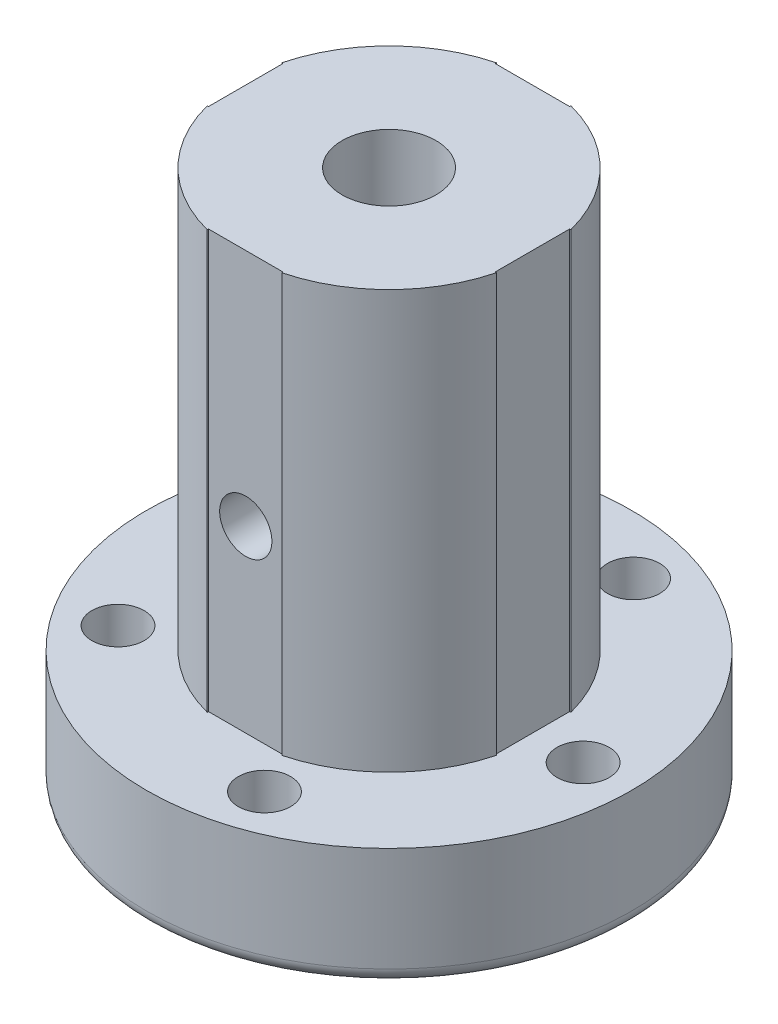
SolidWorks part; units mm, degrees
ref_plane "Front Plane" through (0, 0, 0) normal (0, 0, 1) x (1, 0, 0)
ref_plane "Top Plane" through (0, 0, 0) normal (0, 1, 0) x (1, 0, 0)
ref_plane "Right Plane" through (0, 0, 0) normal (1, 0, 0) x (0, 0, -1)
sketch "Sketch1" plane through (0, 0, 0) normal (0, 1, 0) x (1, 0, 0)
  circle A0 centre (0, 0) radius 16.25
  dimension "D1" = 32.5
extrude "Boss-Extrude1" add sketch "Sketch1" along normal blind 8
sketch "Sketch2" plane through (0, 8, 0) normal (0, 1, 0) x (1, 0, 0)
  circle A0 centre (0, 0) radius 10
  dimension "D1" = 20
extrude "Boss-Extrude2" add sketch "Sketch2" along normal blind 28
sketch "Sketch3" plane through (0, 36, 0) normal (0, 1, 0) x (1, 0, 0)
  circle A0 centre (0, 0) radius 3.15
  dimension "D1" = 6.3
extrude "Cut-Extrude1" cut sketch "Sketch3" against normal blind 25
sketch "Sketch4" plane through (0, 36, 0) normal (0, 1, 0) x (1, 0, 0)
  line L1 (9.6, 2.5) -> (10.7935, 2.5)
  line L2 (9.6, 2.5) -> (9.6, -2.5)
  line L3 (9.6, -2.5) -> (10.7935, -2.5)
  line L4 (10.7935, 2.5) -> (10.7935, -2.5)
  dimension "D1" = 9.6
  dimension "D2" = 5
  dimension "D3" = 2.5
extrude "Cut-Extrude2" cut sketch "Sketch4" against normal blind 28
pattern_circular "CirPattern1" count 4 over 360 about axis through (0, 0, 0) along (0, 1, 0) of "Cut-Extrude2"
sketch "Sketch5" plane through (0, 0, -9.6) normal (0, 0, -1) x (-1, 0, 0)
  line L0 (10, 8) -> (-10, 8) construction
  circle A0 centre (0, 20) radius 1.75
  dimension "D1" = 3.5
  dimension "D2" = 12
extrude "Cut-Extrude3" cut sketch "Sketch5" against normal blind 25
fillet "Fillet1" radius 1 1 edges at (0, 0, 16.25)
sketch "Sketch6" plane through (0, 0, 0) normal (0, -1, 0) x (-1, 0, 0)
  circle A0 centre (0, 0) radius 1.75
  dimension "D1" = 3.5
extrude "Cut-Extrude4" cut sketch "Sketch6" against normal blind 25
sketch "Sketch7" plane through (0, 0, 0) normal (0, -1, 0) x (-1, 0, 0)
  circle A0 centre (-13, 0) radius 1.75
  circle A1 centre (0, 0) radius 1.75 construction
  dimension "D1" = 3.5
  dimension "D2" = 13
extrude "Cut-Extrude5" cut sketch "Sketch7" against normal blind 10
pattern_circular "CirPattern2" count 5 over 360 about axis through (0, 0, 0) along (0, 1, 0) of "Cut-Extrude5"
